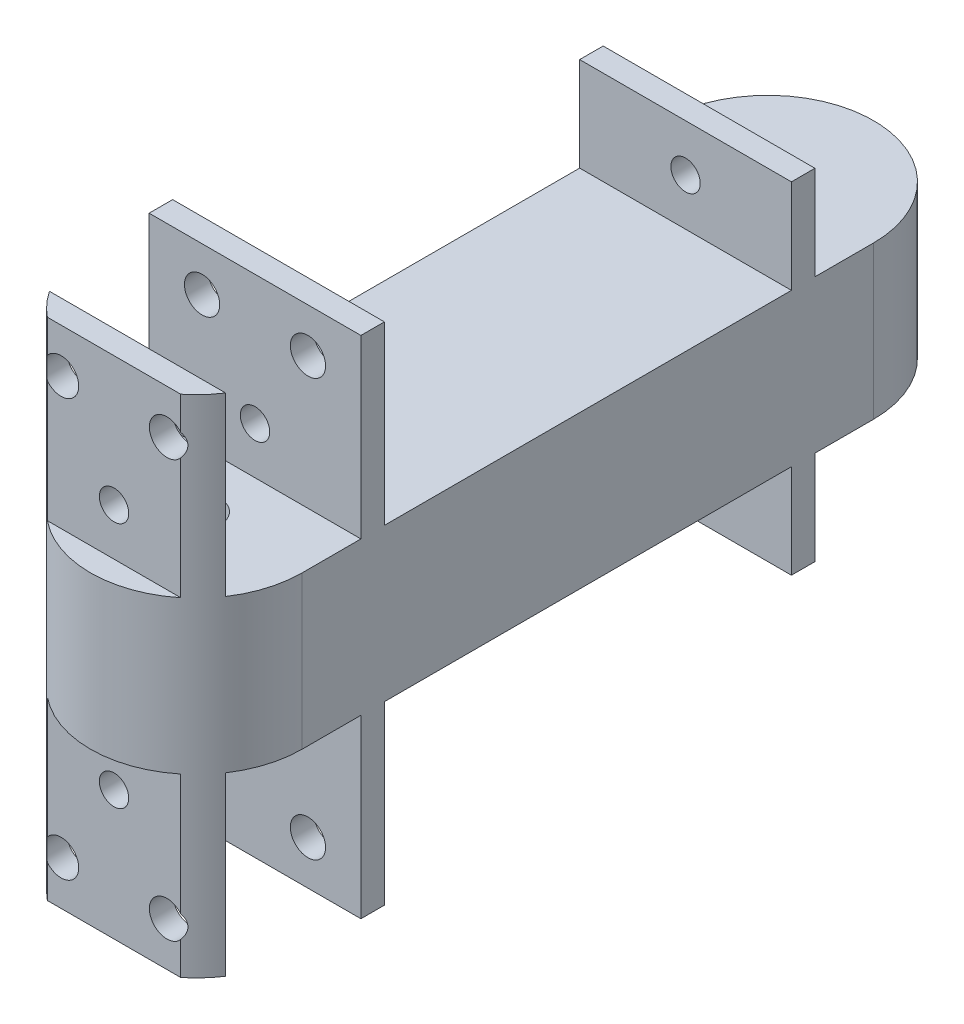
SolidWorks part; units mm, degrees
ref_plane "Front Plane" through (0, 0, 0) normal (0, 0, 1) x (1, 0, 0)
ref_plane "Top Plane" through (0, 0, 0) normal (0, 1, 0) x (1, 0, 0)
ref_plane "Right Plane" through (0, 0, 0) normal (1, 0, 0) x (0, 0, -1)
sketch "Sketch1" plane through (0, 0, 0) normal (0, 1, 0) x (1, 0, 0)
  line L0 (0, 0) -> (0, 97.29) construction
  line L1 (0, 0) -> (0, 97.29) construction
  line L2 (-8.025, 0) -> (-8.025, 97.29) construction
  line L3 (8.025, 0) -> (8.025, 97.29) construction
  line L4 (-18.025, 0) -> (-18.025, 97.29)
  line L5 (18.025, 0) -> (18.025, 97.29)
  line L6 (18.025, 48.645) -> (-18.025, 48.645) construction
  circle A0 centre (0, 0) radius 8.025 construction
  arc A1 (-8.025, 0) -> (8.025, 0) centre (0, 0) ccw construction
  arc A2 (8.025, 97.29) -> (-8.025, 97.29) centre (0, 97.29) ccw construction
  arc A3 (18.025, 97.29) -> (-18.025, 97.29) centre (0, 97.29) ccw
  arc A4 (-18.025, 0) -> (18.025, 0) centre (0, 0) ccw
  circle A5 centre (0, 0) radius 4
  circle A6 centre (0, 97.29) radius 4
  point P3 (0, 48.645)
  dimension "D1" = 16.05
  dimension "D4" = 8
  dimension "D2" = 97.29
  dimension "D3" = 10
extrude "Boss-Extrude1" add sketch "Sketch1" along normal blind 3
sketch "Sketch3" plane through (0, 3, 0) normal (0, 1, 0) x (1, 0, 0)
  line L1 (-15.025, 0) -> (-18.025, 0)
  line L2 (15.025, 0) -> (15.025, 97.29)
  line L3 (18.025, 0) -> (18.025, 97.29)
  line L4 (0, 97.011) -> (0, 112.315) construction
  line L5 (0, 112.315) -> (0, 115.315)
  arc A2 (15.025, 97.29) -> (-15.025, 97.29) centre (0, 97.29) ccw
  arc A3 (15.025, 97.29) -> (0, 112.315) centre (0, 97.29) ccw
  arc A4 (0, 115.315) -> (18.025, 97.29) centre (0, 97.29) cw
  arc A5 (-15.025, 0) -> (15.025, 0) centre (0, 0) ccw
  arc A6 (-15.025, 0) -> (15.025, 0) centre (0, 0) ccw
  arc A7 (-18.025, 0) -> (18.025, 0) centre (0, 0) ccw
  arc A8 (18.025, 97.29) -> (-18.025, 97.29) centre (0, 97.29) ccw construction
  point P4 (0, 0)
  dimension "D1" = 3
  dimension "D2" = 3
extrude "Boss-Extrude3" add sketch "Sketch3" along normal blind 20
ref_plane "Plane1" through (0, 13, 0) normal (0, 1, 0) x (1, 0, 0)
mirror "Mirror1" about plane through (0, 13, 0) normal (0, 1, 0) of "Boss-Extrude1"
sketch "Sketch4" plane through (0, 0, 0) normal (0, -1, 0) x (1, 0, 0)
  line L0 (-18.025, -97.29) -> (-18.025, 0) construction
  line L1 (-18.025, -10) -> (18.025, -10)
  line L2 (-18.025, -10) -> (-18.025, -14)
  line L3 (-18.025, -14) -> (18.025, -14)
  line L4 (18.025, -10) -> (18.025, -14)
  line L5 (18.025, 0) -> (18.025, -97.29) construction
  line L6 (-18.025, 0) -> (18.025, 0) construction
  line L7 (-14.9967, 10) -> (14.9967, 10)
  line L8 (-18.025, 10) -> (18.025, 10) construction
  line L9 (-11.3534, 14) -> (11.3534, 14)
  line L10 (0, 14) -> (0, 10) construction
  line L11 (-18.025, -48.645) -> (18.025, -48.645) construction
  arc A0 (18.025, 0) -> (-18.025, 0) centre (0, 0) ccw construction
  arc A1 (11.3534, 14) -> (14.9967, 10) centre (0, 0) cw
  arc A2 (-11.3534, 14) -> (-14.9967, 10) centre (0, 0) ccw
  dimension "D1" = 4
  dimension "D2" = 10
  dimension "D3" = 10
extrude "Boss-Extrude4" add sketch "Sketch4" along normal blind 30
sketch "Sketch5" plane through (0, 0, -14) normal (0, 0, -1) x (-1, 0, 0)
  line L0 (-18.025, 0) -> (0, -8) construction
  line L1 (18.025, -15) -> (-18.025, -15) construction
  line L2 (18.025, -30) -> (18.025, 0) construction
  line L3 (-18.025, -30) -> (-18.025, 0) construction
  line L4 (-18.025, -15) -> (0, -30) construction
  line L5 (18.025, -30) -> (-18.025, -30) construction
  line L6 (0, -30) -> (0, -15) construction
  circle A0 centre (0, -8) radius 2.5
  circle A1 centre (-9.0125, -22.5) radius 3
  circle A2 centre (9.0125, -22.5) radius 3
  dimension "D1" = 5
  dimension "D3" = 6
  dimension "D2" = 8
sketch "Sketch6" plane through (0, 0, 0) normal (0, -1, 0) x (1, 0, 0)
  line L6 (18.025, 0) -> (18.025, -97.29) construction
  line L7 (-18.025, -14) -> (18.025, -14)
  line L8 (-18.025, -14) -> (-18.025, -10)
  line L9 (-18.025, -10) -> (18.025, -10)
  line L10 (18.025, -14) -> (18.025, -10)
  line L13 (18.025, -48.645) -> (-18.025, -48.645) construction
  line L14 (-18.025, -97.29) -> (-18.025, -14) construction
  line L15 (18.025, -83.29) -> (18.025, -87.29)
  line L16 (-18.025, -87.29) -> (18.025, -87.29)
  line L17 (-18.025, -83.29) -> (-18.025, -87.29)
  line L18 (-18.025, -83.29) -> (18.025, -83.29)
extrude "Boss-Extrude5" add sketch "Sketch6" along normal blind 16
extrude "Cut-Extrude2" cut sketch "Sketch5" against normal up to surface and the other way up to surface up to face at (0, -15, 14) other way up to face at (0, -8, -87.29)
mirror "Mirror3" about plane through (0, 13, 0) normal (0, 1, 0) of "Cut-Extrude2", "Boss-Extrude5", "Boss-Extrude4"
